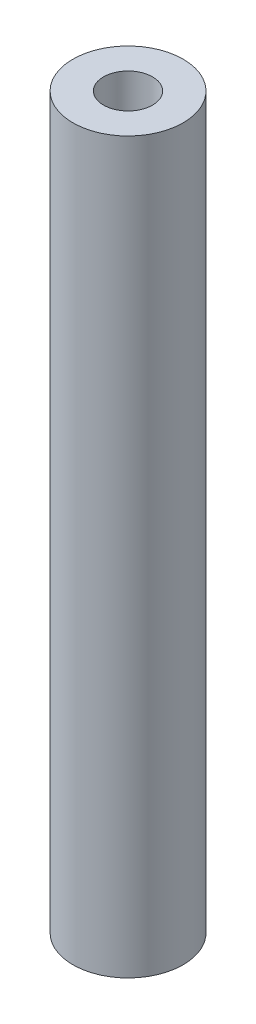
SolidWorks part; units mm, degrees
ref_plane "Front Plane" through (0, 0, 0) normal (0, 0, 1) x (1, 0, 0)
ref_plane "Top Plane" through (0, 0, 0) normal (0, 1, 0) x (1, 0, 0)
ref_plane "Right Plane" through (0, 0, 0) normal (1, 0, 0) x (0, 0, -1)
sketch "Sketch1" plane through (0, 0, 0) normal (0, 1, 0) x (1, 0, 0)
  circle A0 centre (0, 0) radius 1.2
  circle A1 centre (0, 0) radius 2.7
  dimension "D1" = 2.4
  dimension "D2" = 1.5
extrude "Boss-Extrude1" add sketch "Sketch1" along normal blind 35.7
